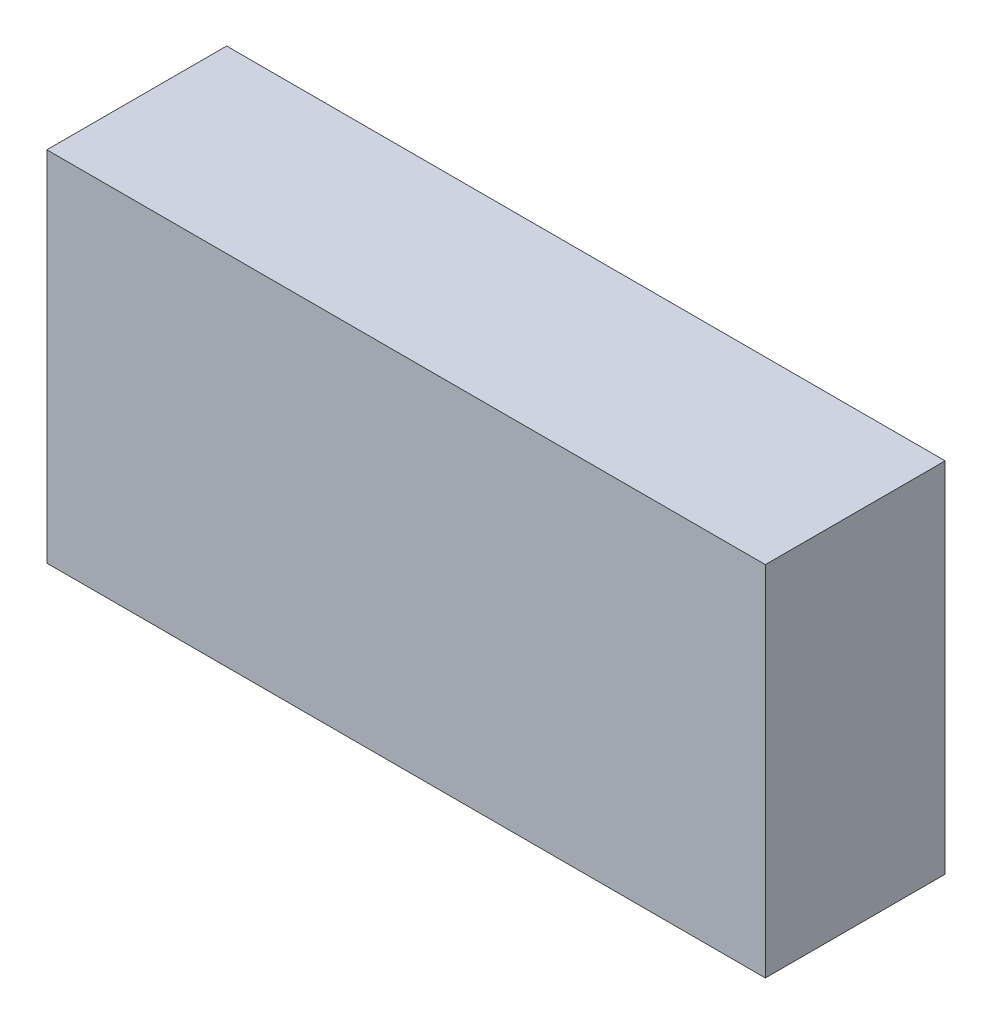
SolidWorks part; units mm, degrees
ref_plane "Ebene vorne" through (0, 0, 0) normal (0, 0, 1) x (1, 0, 0)
ref_plane "Ebene oben" through (0, 0, 0) normal (0, 1, 0) x (1, 0, 0)
ref_plane "Ebene rechts" through (0, 0, 0) normal (1, 0, 0) x (0, 0, -1)
sketch "Skizze1" plane through (0, 0, 0) normal (0, 0, 1) x (1, 0, 0)
  line L0 (-1.9984, 1.0084) -> (1.9984, 1.0084)
  line L1 (1.9984, 1.0084) -> (1.9984, -0.983)
  line L2 (1.9984, -0.983) -> (-1.9984, -0.983)
  line L3 (-1.9984, -0.983) -> (-1.9984, 1.0084)
extrude "Component_Outline" add sketch "Skizze1" along normal blind 1 separate body
sketch3d "3D-Skizze1"
  line L0 (0, 0, 0) -> (1, 0, 0)
  line L1 (0, 0, 0) -> (0, 1, 0)
  line L2 (0, 0, 0) -> (0, 0, 1)
  point P0 (0, 0, 0)
